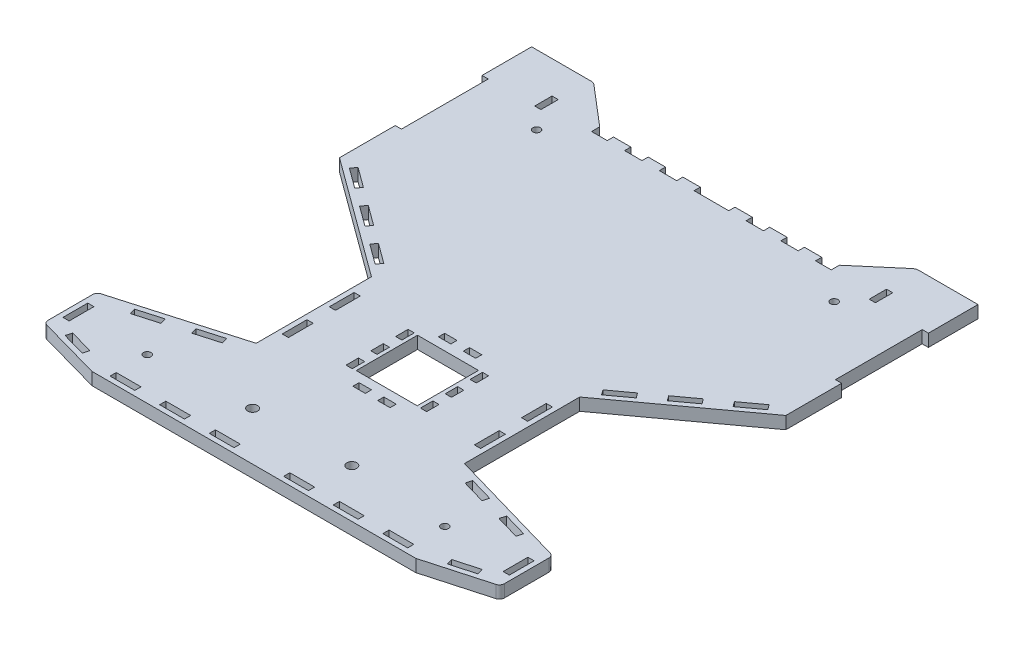
SolidWorks part; units mm, degrees
material "Beech"
ref_plane "Front" through (0, 0, 0) normal (0, 0, 1) x (1, 0, 0)
ref_plane "Top" through (0, 0, 0) normal (0, 1, 0) x (1, 0, 0)
ref_plane "Right" through (0, 0, 0) normal (1, 0, 0) x (0, 0, -1)
sketch "Sketch1" plane through (0, 0, 0) normal (0, 1, 0) x (1, 0, 0)
  line L0 (47.4037, 85) -> (-47.4037, 85) construction
  line L1 (-90, -100) -> (90, -100) construction
  line L2 (-90, -100) -> (-90, 100) construction
  line L3 (-90, 100) -> (90, 100) construction
  line L4 (90, -100) -> (90, 100) construction
  line L5 (-90, -100) -> (90, 100) construction
  line L6 (-90, 100) -> (90, -100) construction
  line L7 (-47.4037, 85) -> (-64.159, 99.2831)
  line L8 (-66.1052, 100) -> (-90, 100) construction
  line L9 (-90, 100) -> (-90, 22.5219)
  line L10 (-90, 25) -> (-40, -11.5806) construction
  line L11 (-40, -11.5806) -> (-40, -60.5806) construction
  line L13 (-90, -56.5958) -> (-90, -100) construction
  line L14 (-90, -100) -> (90, -100) construction
  line L15 (0, 23.9102) -> (0, -23.5083) construction
  line L16 (90, -75) -> (90, -100) construction
  line L17 (40, -60.5806) -> (90, -75) construction
  line L18 (40, -11.5806) -> (40, -60.5806) construction
  line L20 (90, 100) -> (90, 25)
  line L21 (66.1052, 100) -> (90, 100) construction
  line L22 (47.4037, 85) -> (64.159, 99.2831)
  line L23 (2.5, -17.5806) -> (7.5, -17.5806)
  line L24 (-12.3, -48.4306) -> (12.3, -48.4306)
  line L25 (-12.3, -48.4306) -> (-12.3, -23.7306)
  line L26 (-12.3, -23.7306) -> (12.3, -23.7306)
  line L27 (12.3, -48.4306) -> (12.3, -23.7306)
  line L28 (-12.3, -48.4306) -> (12.3, -23.7306) construction
  line L29 (-12.3, -23.7306) -> (12.3, -48.4306) construction
  line L30 (-15, -53.3306) -> (15, -53.3306) construction
  line L31 (-15, -53.3306) -> (-15, -18.8306) construction
  line L32 (-15, -18.8306) -> (15, -18.8306) construction
  line L33 (15, -53.3306) -> (15, -18.8306) construction
  line L34 (-15, -53.3306) -> (15, -18.8306) construction
  line L35 (-15, -18.8306) -> (15, -53.3306) construction
  line L36 (-7.5, -20.0806) -> (-2.5, -20.0806)
  line L37 (-7.5, -20.0806) -> (-7.5, -17.5806)
  line L38 (-7.5, -17.5806) -> (-2.5, -17.5806)
  line L39 (-2.5, -20.0806) -> (-2.5, -17.5806)
  line L40 (-7.5, -20.0806) -> (-2.5, -17.5806) construction
  line L41 (-7.5, -17.5806) -> (-2.5, -20.0806) construction
  line L42 (7.5, -20.0806) -> (7.5, -17.5806)
  line L43 (2.5, -20.0806) -> (7.5, -20.0806)
  line L44 (2.5, -20.0806) -> (2.5, -17.5806)
  line L53 (15.0031, -36.0806) -> (3.8557, -36.0806) construction
  line L62 (-7.5, -54.5806) -> (-2.5, -54.5806)
  line L63 (-2.5, -52.0806) -> (-2.5, -54.5806)
  line L64 (-7.5, -52.0806) -> (-2.5, -52.0806)
  line L65 (-7.5, -52.0806) -> (-7.5, -54.5806)
  line L66 (2.5, -52.0806) -> (2.5, -54.5806)
  line L67 (2.5, -52.0806) -> (7.5, -52.0806)
  line L68 (7.5, -52.0806) -> (7.5, -54.5806)
  line L69 (2.5, -54.5806) -> (7.5, -54.5806)
  line L70 (-16.25, -33.5806) -> (-16.25, -38.5806)
  line L71 (-13.75, -23.5806) -> (-16.25, -23.5806)
  line L72 (-13.75, -23.5806) -> (-13.75, -28.5806)
  line L73 (-13.75, -28.5806) -> (-16.25, -28.5806)
  line L74 (-16.25, -23.5806) -> (-16.25, -28.5806)
  line L75 (-13.75, -23.5806) -> (-16.25, -28.5806) construction
  line L76 (-13.75, -28.5806) -> (-16.25, -23.5806) construction
  line L77 (-13.75, -38.5806) -> (-16.25, -38.5806)
  line L78 (-13.75, -33.5806) -> (-13.75, -38.5806)
  line L79 (-13.75, -33.5806) -> (-16.25, -33.5806)
  line L80 (-16.25, -43.5806) -> (-16.25, -48.5806)
  line L81 (-13.75, -48.5806) -> (-16.25, -48.5806)
  line L82 (-13.75, -43.5806) -> (-13.75, -48.5806)
  line L83 (-13.75, -43.5806) -> (-16.25, -43.5806)
  line L88 (13.75, -28.5806) -> (16.25, -28.5806)
  line L89 (16.25, -23.5806) -> (16.25, -28.5806)
  line L90 (13.75, -23.5806) -> (16.25, -23.5806)
  line L91 (13.75, -23.5806) -> (13.75, -28.5806)
  line L92 (13.75, -33.5806) -> (16.25, -33.5806)
  line L93 (13.75, -33.5806) -> (13.75, -38.5806)
  line L94 (13.75, -38.5806) -> (16.25, -38.5806)
  line L95 (16.25, -33.5806) -> (16.25, -38.5806)
  line L96 (13.75, -43.5806) -> (16.25, -43.5806)
  line L97 (13.75, -43.5806) -> (13.75, -48.5806)
  line L98 (13.75, -48.5806) -> (16.25, -48.5806)
  line L99 (16.25, -43.5806) -> (16.25, -48.5806)
  line L104 (-90, 45) -> (-87.5, 45)
  line L105 (90, 80) -> (87.5, 80)
  line L106 (90, 80) -> (90, 45)
  line L107 (90, 45) -> (87.5, 45)
  line L108 (87.5, 80) -> (87.5, 45)
  line L109 (90, 80) -> (87.5, 45) construction
  line L110 (90, 45) -> (87.5, 80) construction
  line L111 (-87.5, 80) -> (-87.5, 45)
  line L112 (-90, 80) -> (-87.5, 80)
  line L113 (-90, 80) -> (-90, 45)
  line L114 (-16.25, -53.5806) -> (-16.25, -58.5806) [skipped]
  line L115 (-13.75, -58.5806) -> (-16.25, -58.5806) [skipped]
  line L116 (-13.75, -53.5806) -> (-13.75, -58.5806) [skipped]
  line L117 (-13.75, -53.5806) -> (-16.25, -53.5806) [skipped]
  line L118 (12.5, -17.5806) -> (17.5, -17.5806) [skipped]
  line L119 (17.5, -20.0806) -> (17.5, -17.5806) [skipped]
  line L120 (12.5, -20.0806) -> (17.5, -20.0806) [skipped]
  line L121 (12.5, -20.0806) -> (12.5, -17.5806) [skipped]
  line L122 (22.5, -17.5806) -> (27.5, -17.5806) [skipped]
  line L123 (27.5, -20.0806) -> (27.5, -17.5806) [skipped]
  line L124 (22.5, -20.0806) -> (27.5, -20.0806) [skipped]
  line L125 (22.5, -20.0806) -> (22.5, -17.5806) [skipped]
  line L126 (-66.1052, 100) -> (-90, 100)
  line L127 (66.1052, 100) -> (90, 100)
  line L128 (-48.3247, 82.5) -> (48.3247, 82.5) construction
  line L143 (48.3247, 82.5) -> (42, 82.5)
  line L144 (42, 82.5) -> (42, 85)
  line L145 (42, 85) -> (35, 85)
  line L146 (35, 85) -> (35, 82.5)
  line L147 (35, 82.5) -> (28, 82.5)
  line L148 (28, 82.5) -> (28, 85)
  line L149 (28, 85) -> (21, 85)
  line L150 (21, 85) -> (21, 82.5)
  line L151 (21, 82.5) -> (14, 82.5)
  line L152 (14, 82.5) -> (14, 85)
  line L153 (14, 85) -> (7, 85)
  line L154 (7, 85) -> (7, 82.5)
  line L155 (7, 82.5) -> (-7, 82.5)
  line L156 (-7, 82.5) -> (-7, 85)
  line L157 (-7, 85) -> (-14, 85)
  line L158 (-14, 85) -> (-14, 82.5)
  line L159 (-14, 82.5) -> (-21, 82.5)
  line L160 (-21, 82.5) -> (-21, 85)
  line L161 (-21, 85) -> (-28, 85)
  line L162 (-28, 85) -> (-28, 82.5)
  line L163 (-28, 82.5) -> (-35, 82.5)
  line L164 (-35, 82.5) -> (-35, 85)
  line L165 (-42, 85) -> (-42, 82.5)
  line L166 (-42, 82.5) -> (-48.3247, 82.5)
  line L179 (-35, 85) -> (-42, 85)
  line L186 (48.3247, 82.5) -> (48.3247, 85.7851)
  line L187 (-48.3247, 82.5) -> (-48.3247, 85.7851)
  line L188 (-90, 28.0976) -> (-40, -8.483) construction
  line L189 (-40, -8.483) -> (-40, -11.5806) construction
  line L190 (-45.6495, -7.4474) -> (-53.7201, -1.5428)
  line L191 (-45.6495, -7.4474) -> (-44.1733, -5.4298)
  line L192 (-44.1733, -5.4298) -> (-52.244, 0.4749)
  line L193 (-52.244, 0.4749) -> (-53.7201, -1.5428)
  line L194 (-60.9647, 3.7574) -> (-69.0353, 9.662)
  line L195 (-60.9647, 3.7574) -> (-59.4885, 5.775)
  line L196 (-59.4885, 5.775) -> (-67.5592, 11.6796)
  line L197 (-67.5592, 11.6796) -> (-69.0353, 9.662)
  line L198 (-76.2799, 14.9622) -> (-84.3505, 20.8668)
  line L199 (-76.2799, 14.9622) -> (-74.8037, 16.9798)
  line L200 (-74.8037, 16.9798) -> (-82.8744, 22.8844)
  line L201 (-82.8744, 22.8844) -> (-84.3505, 20.8668)
  line L202 (40, -8.483) -> (40, -11.5806) construction
  line L203 (90, 28.0976) -> (40, -8.483) construction
  line L204 (90, 25) -> (40, -11.5806) construction
  line L205 (40, -14.0588) -> (90, 22.5219)
  line L206 (82.8744, 22.8844) -> (84.3505, 20.8668)
  line L207 (74.8037, 16.9798) -> (82.8744, 22.8844)
  line L208 (76.2799, 14.9622) -> (74.8037, 16.9798)
  line L209 (76.2799, 14.9622) -> (84.3505, 20.8668)
  line L210 (67.5592, 11.6796) -> (69.0353, 9.662)
  line L211 (59.4885, 5.775) -> (67.5592, 11.6796)
  line L212 (60.9647, 3.7574) -> (59.4885, 5.775)
  line L213 (60.9647, 3.7574) -> (69.0353, 9.662)
  line L214 (52.244, 0.4749) -> (53.7201, -1.5428)
  line L215 (44.1733, -5.4298) -> (52.244, 0.4749)
  line L216 (45.6495, -7.4474) -> (44.1733, -5.4298)
  line L217 (45.6495, -7.4474) -> (53.7201, -1.5428)
  line L218 (40, -14.0588) -> (40, -60.5806) construction
  line L219 (-40, -14.0588) -> (-90, 22.5219)
  line L220 (90, 22.5219) -> (90, 25)
  line L221 (-40, -31.5806) -> (-37.5, -21.5806) construction
  line L222 (42, -12.5955) -> (42, -61.1574)
  line L223 (37.5, -11.5806) -> (37.5, -62.4616) construction
  line L224 (40, -40.5806) -> (40, -50.5806)
  line L225 (40, -21.5806) -> (37.5, -21.5806)
  line L226 (40, -21.5806) -> (40, -31.5806)
  line L227 (40, -31.5806) -> (37.5, -31.5806)
  line L228 (37.5, -21.5806) -> (37.5, -31.5806)
  line L229 (40, -21.5806) -> (37.5, -31.5806) construction
  line L230 (40, -31.5806) -> (37.5, -21.5806) construction
  line L231 (40, -50.5806) -> (37.5, -50.5806)
  line L232 (37.5, -40.5806) -> (37.5, -50.5806)
  line L233 (40, -40.5806) -> (37.5, -40.5806)
  line L234 (-40, -21.5806) -> (-37.5, -31.5806) construction
  line L235 (-37.5, -11.5806) -> (-37.5, -62.4616) construction
  line L236 (-40, -14.0588) -> (-40, -60.5806) construction
  line L237 (-40, -11.5806) -> (-40, -60.5806) construction
  line L238 (-40, -40.5806) -> (-37.5, -40.5806)
  line L239 (-37.5, -40.5806) -> (-37.5, -50.5806)
  line L240 (-40, -50.5806) -> (-37.5, -50.5806)
  line L241 (-37.5, -21.5806) -> (-37.5, -31.5806)
  line L242 (-40, -31.5806) -> (-37.5, -31.5806)
  line L243 (-40, -21.5806) -> (-40, -31.5806)
  line L244 (-40, -21.5806) -> (-37.5, -21.5806)
  line L245 (-40, -40.5806) -> (-40, -50.5806)
  line L246 (-42, -12.5955) -> (-42, -61.1574)
  line L247 (90, -75) -> (90, -93) construction
  line L248 (90, -93) -> (65, -100) construction
  line L249 (65, -100) -> (-65, -100) construction
  line L250 (-49.2621, -64.5526) -> (-58.8705, -67.3236) construction
  line L251 (-54.4126, -64.7371) -> (-53.7199, -67.1392) construction
  line L252 (42, -59.0759) -> (92, -73.4953)
  line L253 (92, -73.4953) -> (92, -94.5169)
  line L254 (92, -94.5169) -> (65.2747, -102)
  line L255 (65.2747, -102) -> (-65.2747, -102)
  line L256 (37.5, -62.4616) -> (87.5, -76.8809) construction
  line L257 (87.5, -76.8809) -> (87.5, -91.1038) construction
  line L258 (87.5, -91.1038) -> (64.6566, -97.5) construction
  line L259 (64.6566, -97.5) -> (-64.6566, -97.5) construction
  line L260 (48.9157, -65.7537) -> (49.6084, -63.3516)
  line L261 (48.9157, -65.7537) -> (58.5241, -68.5246)
  line L262 (49.6084, -63.3516) -> (59.2169, -66.1225)
  line L263 (58.5241, -68.5246) -> (59.2169, -66.1225)
  line L264 (54.4126, -64.7371) -> (53.7199, -67.1392) construction
  line L265 (49.2621, -64.5526) -> (58.8705, -67.3236) construction
  line L266 (68.1325, -71.2956) -> (68.8253, -68.8935)
  line L267 (68.1325, -71.2956) -> (77.741, -74.0665)
  line L268 (77.741, -74.0665) -> (78.4337, -71.6644)
  line L269 (68.8253, -68.8935) -> (78.4337, -71.6644)
  line L270 (87.5, -79) -> (90, -79)
  line L271 (87.5, -79) -> (87.5, -89)
  line L272 (87.5, -89) -> (90, -89)
  line L273 (90, -79) -> (90, -89)
  line L274 (73.6296, -97.5837) -> (72.9555, -95.1763)
  line L275 (73.6296, -97.5837) -> (83.2593, -94.8874)
  line L276 (83.2593, -94.8874) -> (82.5852, -92.48)
  line L277 (72.9555, -95.1763) -> (82.5852, -92.48)
  line L278 (50, -100) -> (50, -97.5)
  line L279 (50, -100) -> (60, -100)
  line L280 (60, -100) -> (60, -97.5)
  line L281 (50, -97.5) -> (60, -97.5)
  line L282 (30, -100) -> (30, -97.5)
  line L283 (30, -97.5) -> (40, -97.5)
  line L284 (40, -100) -> (40, -97.5)
  line L285 (30, -100) -> (40, -100)
  line L286 (10, -100) -> (10, -97.5)
  line L287 (10, -97.5) -> (20, -97.5)
  line L288 (20, -100) -> (20, -97.5)
  line L289 (10, -100) -> (20, -100)
  line L290 (-87.5, -91.1038) -> (-64.6566, -97.5) construction
  line L291 (-87.5, -76.8809) -> (-87.5, -91.1038) construction
  line L292 (-37.5, -62.4616) -> (-87.5, -76.8809) construction
  line L293 (-90, -93) -> (-65, -100) construction
  line L294 (-90, -75) -> (-90, -93) construction
  line L295 (-40, -60.5806) -> (-90, -75) construction
  line L296 (-90, -75) -> (-90, -100) construction
  line L297 (-10, -100) -> (-20, -100)
  line L298 (-20, -100) -> (-20, -97.5)
  line L299 (-10, -97.5) -> (-20, -97.5)
  line L300 (-10, -100) -> (-10, -97.5)
  line L301 (-30, -100) -> (-40, -100)
  line L302 (-40, -100) -> (-40, -97.5)
  line L303 (-30, -97.5) -> (-40, -97.5)
  line L304 (-30, -100) -> (-30, -97.5)
  line L305 (-50, -97.5) -> (-60, -97.5)
  line L306 (-60, -100) -> (-60, -97.5)
  line L307 (-50, -100) -> (-60, -100)
  line L308 (-50, -100) -> (-50, -97.5)
  line L309 (-72.9555, -95.1763) -> (-82.5852, -92.48)
  line L310 (-83.2593, -94.8874) -> (-82.5852, -92.48)
  line L311 (-73.6296, -97.5837) -> (-83.2593, -94.8874)
  line L312 (-73.6296, -97.5837) -> (-72.9555, -95.1763)
  line L313 (-90, -79) -> (-90, -89)
  line L314 (-87.5, -89) -> (-90, -89)
  line L315 (-87.5, -79) -> (-87.5, -89)
  line L316 (-87.5, -79) -> (-90, -79)
  line L317 (-68.8253, -68.8935) -> (-78.4337, -71.6644)
  line L318 (-77.741, -74.0665) -> (-78.4337, -71.6644)
  line L319 (-68.1325, -71.2956) -> (-77.741, -74.0665)
  line L320 (-68.1325, -71.2956) -> (-68.8253, -68.8935)
  line L321 (-58.5241, -68.5246) -> (-59.2169, -66.1225)
  line L322 (-49.6084, -63.3516) -> (-59.2169, -66.1225)
  line L323 (-48.9157, -65.7537) -> (-58.5241, -68.5246)
  line L324 (-48.9157, -65.7537) -> (-49.6084, -63.3516)
  line L325 (-92, -94.5169) -> (-65.2747, -102)
  line L326 (-92, -73.4953) -> (-92, -94.5169)
  line L327 (-42, -59.0759) -> (-92, -73.4953)
  line L328 (-68.7, 79.93) -> (-66.2, 79.93)
  line L329 (68.7, 86.93) -> (66.2, 86.93)
  line L330 (68.7, 86.93) -> (68.7, 79.93)
  line L331 (68.7, 79.93) -> (66.2, 79.93)
  line L332 (66.2, 86.93) -> (66.2, 79.93)
  line L333 (68.7, 86.93) -> (66.2, 79.93) construction
  line L334 (68.7, 79.93) -> (66.2, 86.93) construction
  line L335 (-66.2, 86.93) -> (-66.2, 79.93)
  line L336 (-68.7, 86.93) -> (-66.2, 86.93)
  line L337 (-68.7, 86.93) -> (-68.7, 79.93)
  circle A0 centre (-20, -82.5) radius 2
  circle A1 centre (20, -82.5) radius 2
  circle A4 centre (-60, 72) radius 1.5
  circle A5 centre (-60, -85) radius 1.5
  circle A8 centre (60, -85) radius 1.5
  circle A9 centre (60, 72) radius 1.5
  arc A12 (-64.159, 99.2831) -> (-66.1052, 100) centre (-66.1052, 97) ccw
  arc A13 (66.1052, 100) -> (64.159, 99.2831) centre (66.1052, 97) ccw
  point P0 (0, 0)
  point P6 (67.45, 83.43)
  point P16 (0, -100)
  point P22 (0, 85)
  point P34 (0, -36.0806)
  point P48 (90, -75)
  point P54 (-65, 100)
  point P57 (65, 100)
  point P61 (88.75, 62.5)
  point P64 (90, 62.5)
  point P66 (90, 25)
  point P69 (-90, 25)
  point P70 (0, -36.0806)
  point P76 (-5, -18.8306)
  point P77 (40, -36.0806)
  point P112 (-15, -23.5806)
  point P113 (-15, -26.0806)
  point P199 (0, 82.5)
  point P205 (-65, 6.7097)
  point P219 (38.75, -26.5806)
  point P233 (-38.75, -26.5806)
  point P238 (0, -100)
  point P291 (0, -97.5)
  point P324 (0, -102)
  point P327 (-54.0663, -65.9381)
  point P384 (54.0663, -65.9381)
  dimension "D12" = 4
  dimension "D14" = 3
  dimension "D15" = 2.5
  dimension "D16" = 24.7
  dimension "D30" = 2.5
  dimension "D68" = 30
  dimension "D70" = 3
  dimension "D1" = 200
  dimension "D2" = 180
  dimension "D3" = 25
  dimension "D4" = 75
  dimension "D5" = 49
  dimension "D6" = 50
  dimension "D7" = 11.5806
  dimension "D8" = 15
  dimension "D9" = 25
  dimension "D10" = 42.5963
  dimension "D11" = 17.5
  dimension "D13" = 40
  dimension "D17" = 24.6
  dimension "D18" = 34.5
  dimension "D19" = 30
  dimension "D20" = 2.5
  dimension "D21" = 5
  dimension "D22" = 7.5
  dimension "D23" = 4
  dimension "D24" = 5
  dimension "D25" = 2.5
  dimension "D26" = 5
  dimension "D27" = 4.75
  dimension "D29" = 5
  dimension "D31" = 35
  dimension "D32" = 7
  dimension "D33" = 10
  dimension "D34" = 2.5
  dimension "D35" = 14
  dimension "D36" = 7
  dimension "D37" = 6.3247
  dimension "D38" = 2
  dimension "D39" = 7
  dimension "D40" = 2.5
  dimension "D41" = 2
  dimension "D42" = 2.5
  dimension "D43" = 10
  dimension "D44" = 10
  dimension "D46" = 9
  dimension "D47" = 18
  dimension "D48" = 25
  dimension "D49" = 2.5
  dimension "D50" = 2.5
  dimension "D51" = 2.5
  dimension "D52" = 2
  dimension "D53" = 2
  dimension "D54" = 2
  dimension "D55" = 2
  dimension "D56" = 10
  dimension "D57" = 10
  dimension "D59" = 10
  dimension "D60" = 4
  dimension "D61" = 7
  dimension "D62" = 5
  dimension "D63" = 3
  dimension "D64" = 10
  dimension "D65" = 7
  dimension "D66" = 21.3
  dimension "D67" = 16.57
  dimension "D69" = 15
  dimension "D71" = 28
  dimension "D28" = 4
  dimension "D45" = 2
  dimension "D58" = 2
extrude "Boss-Extrude1" add sketch "Sketch1" along normal blind 5
fillet "Fillet1" radius 2 4 edges at (-92, 2.5, 73.4953) (-92, 2.5, 94.5169) (92, 2.5, 73.4953) (92, 2.5, 94.5169)
